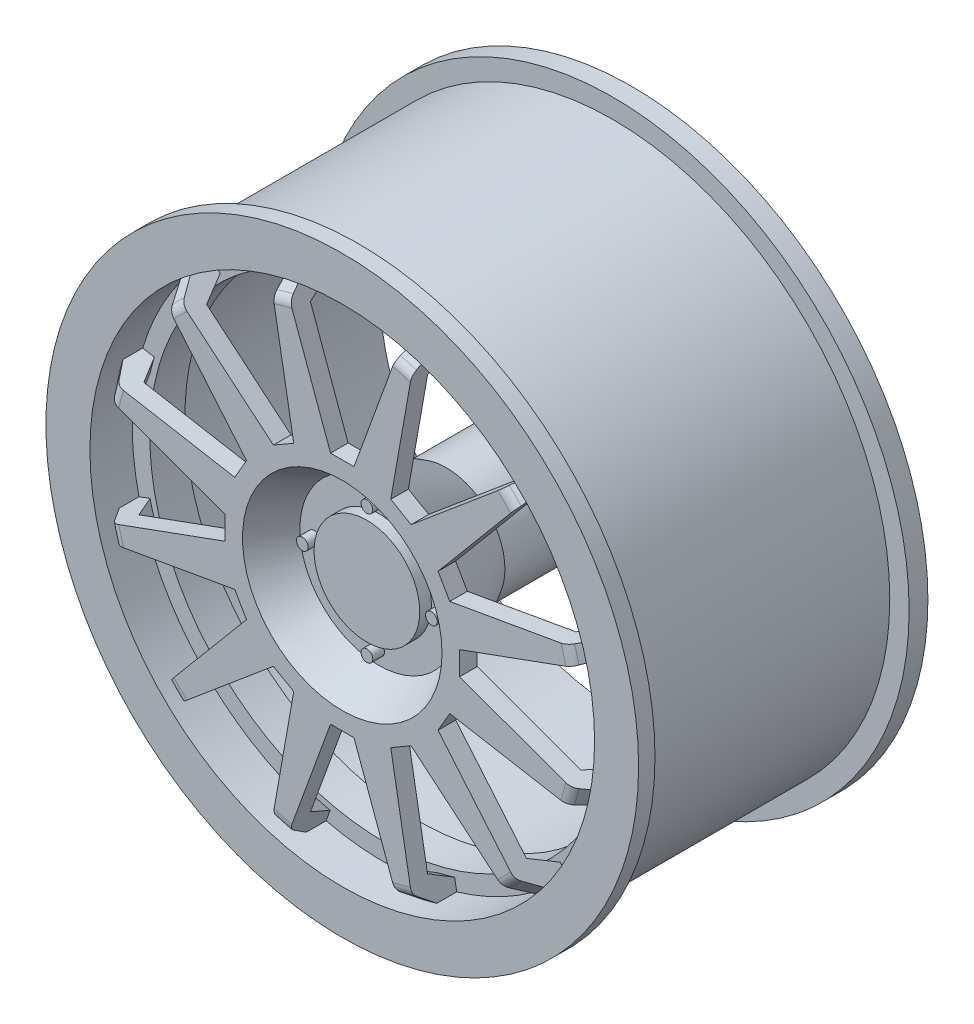
SolidWorks part; units mm, degrees
material "PE High Density"
ref_plane "Front Plane" through (0, 0, 0) normal (0, 0, 1) x (1, 0, 0)
ref_plane "Top Plane" through (0, 0, 0) normal (0, 1, 0) x (1, 0, 0)
ref_plane "Right Plane" through (0, 0, 0) normal (1, 0, 0) x (0, 0, -1)
sketch "Sketch1" plane through (0, 0, 0) normal (1, 0, 0) x (0, 0, -1)
  line L0 (0, 0) -> (32.9054, 0) construction
  line L1 (0, 25.25) -> (0, 21.5)
  line L2 (0, 21.5) -> (3.6, 21.5)
  line L3 (3.6, 21.5) -> (3.6, 20)
  line L4 (3.6, 20) -> (6.6, 20)
  line L5 (6.6, 20) -> (6.6, 21.5)
  line L6 (6.6, 21.5) -> (24.65, 21.5)
  line L7 (24.65, 21.5) -> (24.65, 25.25)
  line L8 (24.65, 25.25) -> (23.05, 25.25)
  line L9 (23.05, 25.25) -> (23.05, 23.6)
  line L10 (23.05, 23.6) -> (1.3953, 23.6)
  line L11 (1.3953, 23.6) -> (1.3953, 25.25)
  line L12 (1.3953, 25.25) -> (0, 25.25)
  dimension "D1" = 24.65
  dimension "D2" = 25.25
  dimension "D3" = 23.6
  dimension "D4" = 21.5
  dimension "D5" = 1.3953
  dimension "D6" = 1.6
  dimension "D7" = 3.6
  dimension "D8" = 3
  dimension "D9" = 20
revolve "Revolve1" add sketch "Sketch1" angle 360 about L0
sketch "Sketch2" plane through (0, 0, 0) normal (1, 0, 0) x (0, 0, -1)
  line L0 (0, 0) -> (27.2, 0) construction
  line L1 (1.5, 0) -> (1.5, 9.25)
  line L2 (1.5, 9.25) -> (8.8612, 5)
  line L3 (8.8612, 5) -> (27.2, 5)
  line L4 (27.2, 5) -> (27.2, 0)
  line L5 (27.2, 0) -> (1.5, 0)
  line L6 (0, 21.5) -> (0, -21.5) construction
  dimension "D1" = 1.5
  dimension "D2" = 9.25
  dimension "D3" = 60
  dimension "D4" = 5
  dimension "D5" = 25.7
revolve "Revolve2" add sketch "Sketch2" angle 360 about L0
sketch "Sketch3" plane through (0, 0, -27.2) normal (0, 0, -1) x (-1, 0, 0)
  line L1 (-2.65, -1.8) -> (2.65, -1.8)
  line L2 (-2.65, -1.8) -> (-2.65, 1.8)
  line L3 (-2.65, 1.8) -> (2.65, 1.8)
  line L4 (2.65, -1.8) -> (2.65, 1.8)
  line L5 (-2.65, -1.8) -> (2.65, 1.8) construction
  line L6 (-2.65, 1.8) -> (2.65, -1.8) construction
  point P0 (0, 0)
  dimension "D1" = 5.3
  dimension "D2" = 3.6
extrude "Cut-Extrude1" cut sketch "Sketch3" against normal blind 22.6
sketch "Sketch4" plane through (0, 0, 0) normal (1, 0, 0) x (0, 0, -1)
  line L0 (3.6, 20.5) -> (3.6, 21.5)
  line L1 (3.6, 21.5) -> (3.6, -21.5) construction
  line L2 (3.6, 20) -> (3.6, -20) construction
  line L3 (3.6, 21.5) -> (1.9155, 21.5)
  line L4 (1.9155, 21.5) -> (0, 20)
  line L5 (0, 21.5) -> (0, -21.5) construction
  line L6 (0, 20) -> (0, 0)
  line L7 (0, 0) -> (1.5, 0)
  line L8 (1.5, 9.25) -> (1.5, -9.25) construction
  line L9 (1.5, 0) -> (1.5, 19.2876)
  line L12 (1.5, 19.2876) -> (3.6, 20.5)
  dimension "D1" = 120
  dimension "D2" = 20.5
  dimension "D3" = 20
  dimension "D4" = 21.5
revolve "Revolve4" add sketch "Sketch4" angle 360 about L7
fillet "Fillet6" radius 1 1 edges at (20, 0, 0)
sketch "Sketch7" plane through (0, 0, 0) normal (0, 0, 1) x (1, 0, 0)
  line L0 (0, 0) -> (0, 25.25) construction
  line L1 (1, 10) -> (-1, 10)
  line L2 (-1, 10) -> (-4.9734, 20.9169)
  line L3 (1, 10) -> (4.9734, 20.9169)
  circle A0 centre (0, 0) radius 25.25 construction
  circle A4 centre (0, 0) radius 21.5 construction
  circle A5 centre (0, 0) radius 21.5
  point P13 (0, 10)
  circle M3 centre (0, 0) radius 19.513
  dimension "D4" = 110
  dimension "D2" = 10
  dimension "D3" = 110
  dimension "D5" = 2
extrude "Cut-Extrude6" cut sketch "Sketch7" against normal blind 3.6 and the other way through all contours L0 A5 L2 M3 | L0 L3 A5 M3 | L0 L1 L3 M3 | L1 L0 L2 M3
pattern_circular "CirPattern1" count 12 over 360 about axis through (0, 0, 0) along (0, 0, 1) of "Cut-Extrude6"
sketch "Sketch9" plane through (0, 0, 0) normal (1, 0, 0) x (0, 0, -1)
  line L0 (0, 0) -> (27.2, 0) construction
  line L1 (27.2, -5) -> (27.2, 5) construction
  line L2 (0, 0) -> (0, 8.5)
  line L3 (0, 5.866) -> (0, 13.2321) construction
  line L4 (0, 8.5) -> (3.1, 6.7102)
  line L5 (3.1, 6.7102) -> (3.1, 0)
  line L6 (3.1, 0) -> (0, 0)
  dimension "D1" = 3.1
  dimension "D2" = 8.5
  dimension "D3" = 60
revolve "Cut-Revolve2" cut sketch "Sketch9" angle 360 about L0
sketch "Sketch10" plane through (0, 0, -3.1) normal (0, 0, 1) x (1, 0, 0)
  circle A0 centre (0, 0) radius 4.5
  circle A1 centre (0, 5.5) radius 0.5
  circle A2 centre (5.5, 0) radius 0.5
  circle A3 centre (0, -5.5) radius 0.5
  circle A4 centre (-5.5, 0) radius 0.5
  point P14 (0, 0)
  dimension "D1" = 9
  dimension "D2" = 1
  dimension "D3" = 5.5
  dimension "D4" = 4
extrude "Boss-Extrude1" add sketch "Sketch10" along normal blind 1
